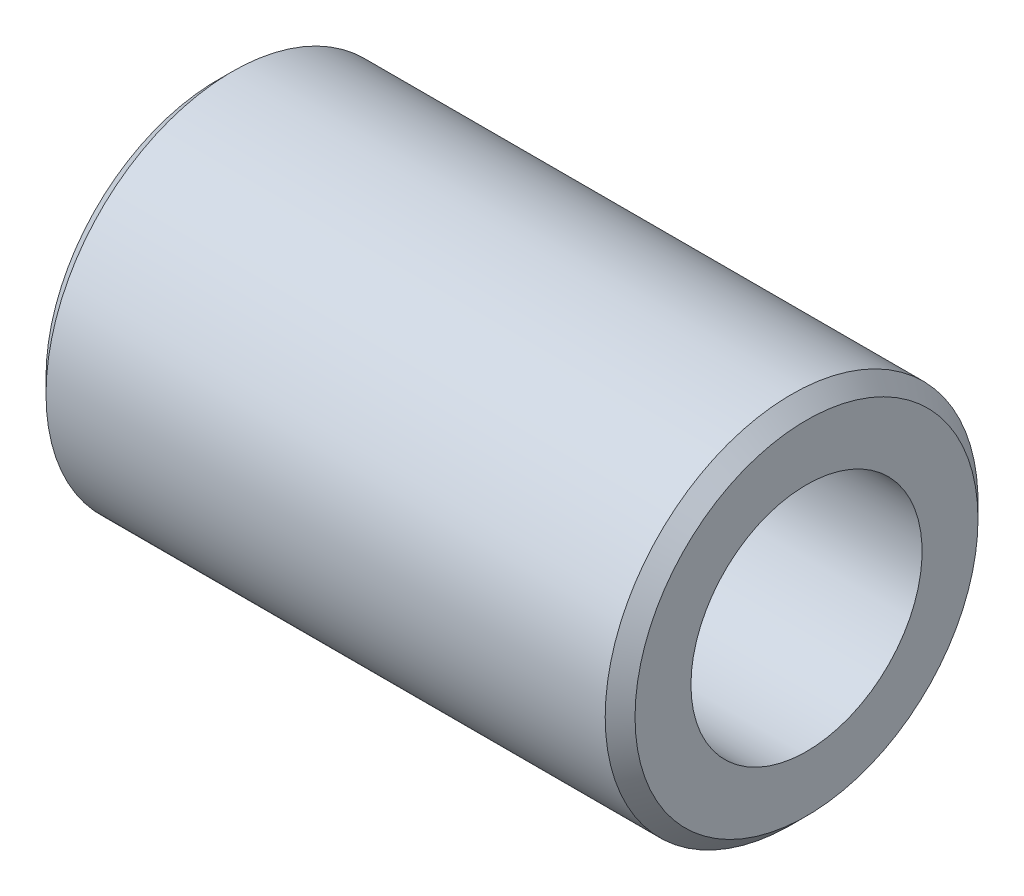
SolidWorks part; units mm, degrees
material "AISI 1020"
ref_plane "Plano frontal" through (0, 0, 0) normal (0, 0, 1) x (1, 0, 0)
ref_plane "Plano superior" through (0, 0, 0) normal (0, 1, 0) x (1, 0, 0)
ref_plane "Plano direito" through (0, 0, 0) normal (1, 0, 0) x (0, 0, -1)
sketch "Esboço1" plane through (0, 0, 0) normal (0, 0, 1) x (1, 0, 0)
  line L0 (-39.5, 0) -> (39.5, 0) construction
  line L1 (-39.5, 23) -> (-37.5, 25)
  line L2 (-39.5, 15.5) -> (39.5, 15.5)
  line L3 (-39.5, 15.5) -> (-39.5, 23)
  line L4 (-37.5, 25) -> (37.5, 25)
  line L5 (39.5, 15.5) -> (39.5, 23)
  line L6 (37.5, 25) -> (39.5, 23)
  point P4 (39.5, 25)
  point P5 (-39.5, 25)
  dimension "D1" = 31
  dimension "D2" = 50
  dimension "D3" = 79
revolve "Revolução1" add sketch "Esboço1" angle 360 about L0
